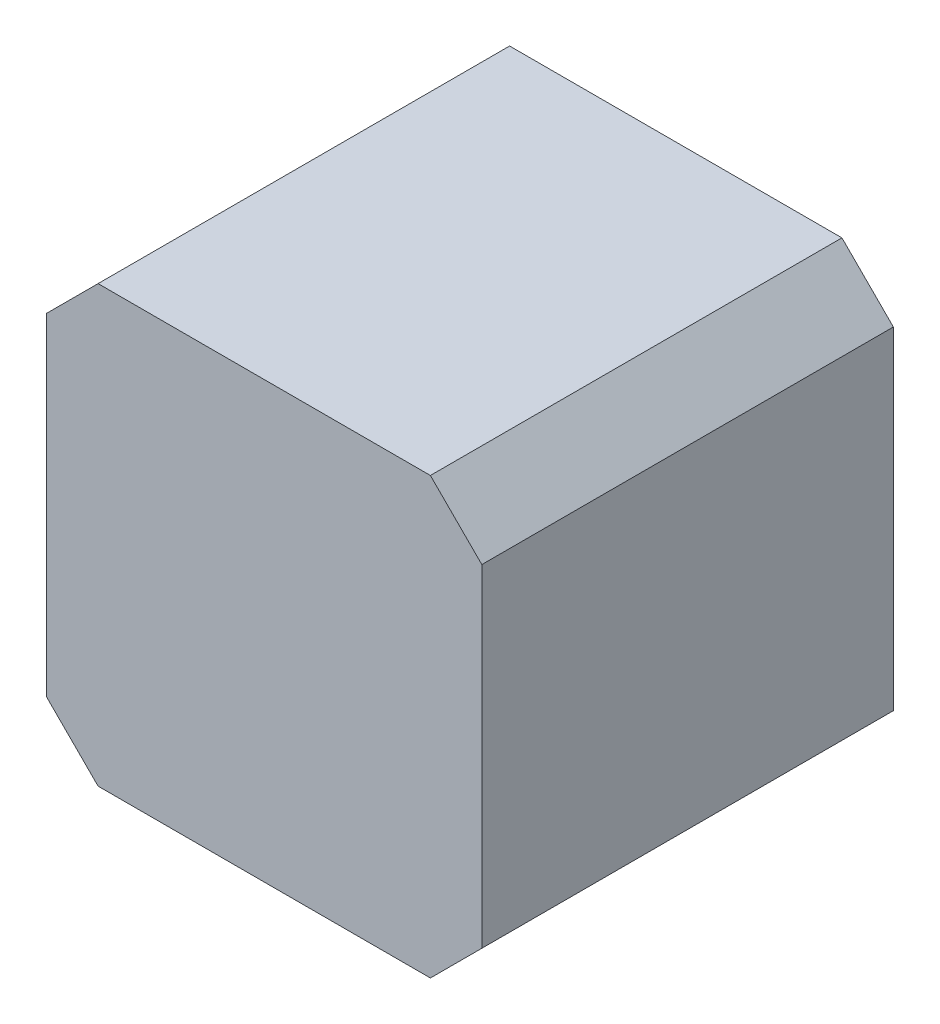
SolidWorks part; units mm, degrees
ref_plane "Front Plane" through (0, 0, 0) normal (0, 0, 1) x (1, 0, 0)
ref_plane "Top Plane" through (0, 0, 0) normal (0, 1, 0) x (1, 0, 0)
ref_plane "Right Plane" through (0, 0, 0) normal (1, 0, 0) x (0, 0, -1)
sketch "Sketch1" plane through (0, 0, 0) normal (0, 0, 1) x (1, 0, 0)
  line L1 (21.15, 21.15) -> (-21.15, 21.15)
  line L2 (21.15, 21.15) -> (21.15, -21.15)
  line L3 (21.15, -21.15) -> (-21.15, -21.15)
  line L4 (-21.15, 21.15) -> (-21.15, -21.15)
  line L5 (21.15, 21.15) -> (-21.15, -21.15) construction
  line L6 (21.15, -21.15) -> (-21.15, 21.15) construction
  point P0 (0, 0)
  dimension "D1" = 42.3
  dimension "D2" = 42.3
extrude "Boss-Extrude1" add sketch "Sketch1" along normal blind 40
chamfer "Chamfer1" distance 5 angle 45 4 edges at (-21.15, -21.15, 20) (21.15, -21.15, 20) (21.15, 21.15, 20) (-21.15, 21.15, 20)
